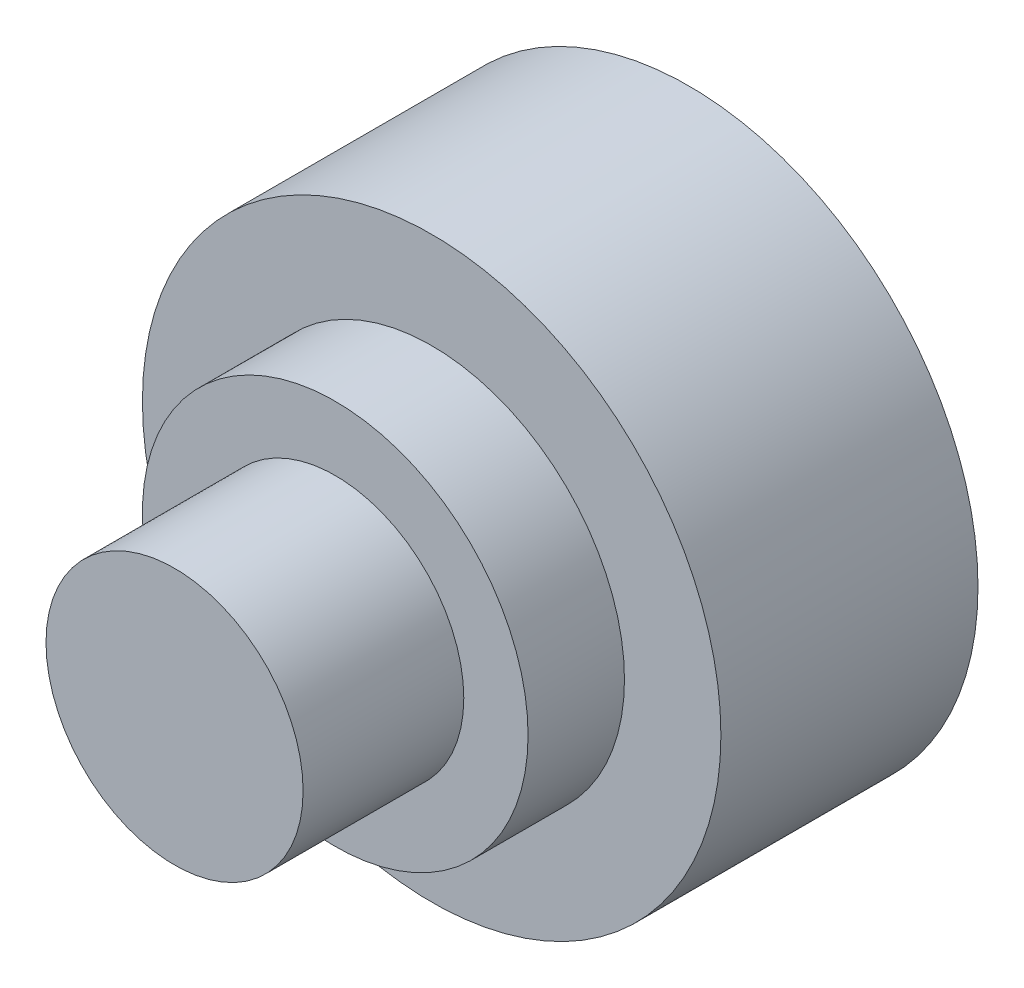
SolidWorks part; units mm, degrees
ref_plane "Front Plane" through (0, 0, 0) normal (0, 0, 1) x (1, 0, 0)
ref_plane "Top Plane" through (0, 0, 0) normal (0, 1, 0) x (1, 0, 0)
ref_plane "Right Plane" through (0, 0, 0) normal (1, 0, 0) x (0, 0, -1)
sketch "Sketch1" plane through (0, 0, 0) normal (0, 0, 1) x (1, 0, 0)
  circle A0 centre (0, 0) radius 9
  dimension "D1" = 18
extrude "Boss-Extrude1" add sketch "Sketch1" along normal blind 8
sketch "Sketch2" plane through (0, 0, 8) normal (0, 0, 1) x (1, 0, 0)
  circle A0 centre (0, 0) radius 6
  dimension "D1" = 12
extrude "Boss-Extrude2" add sketch "Sketch2" along normal blind 3
sketch "Sketch3" plane through (0, 0, 11) normal (0, 0, 1) x (1, 0, 0)
  circle A0 centre (0, 0) radius 4
  dimension "D1" = 8
extrude "Boss-Extrude3" add sketch "Sketch3" along normal blind 5
